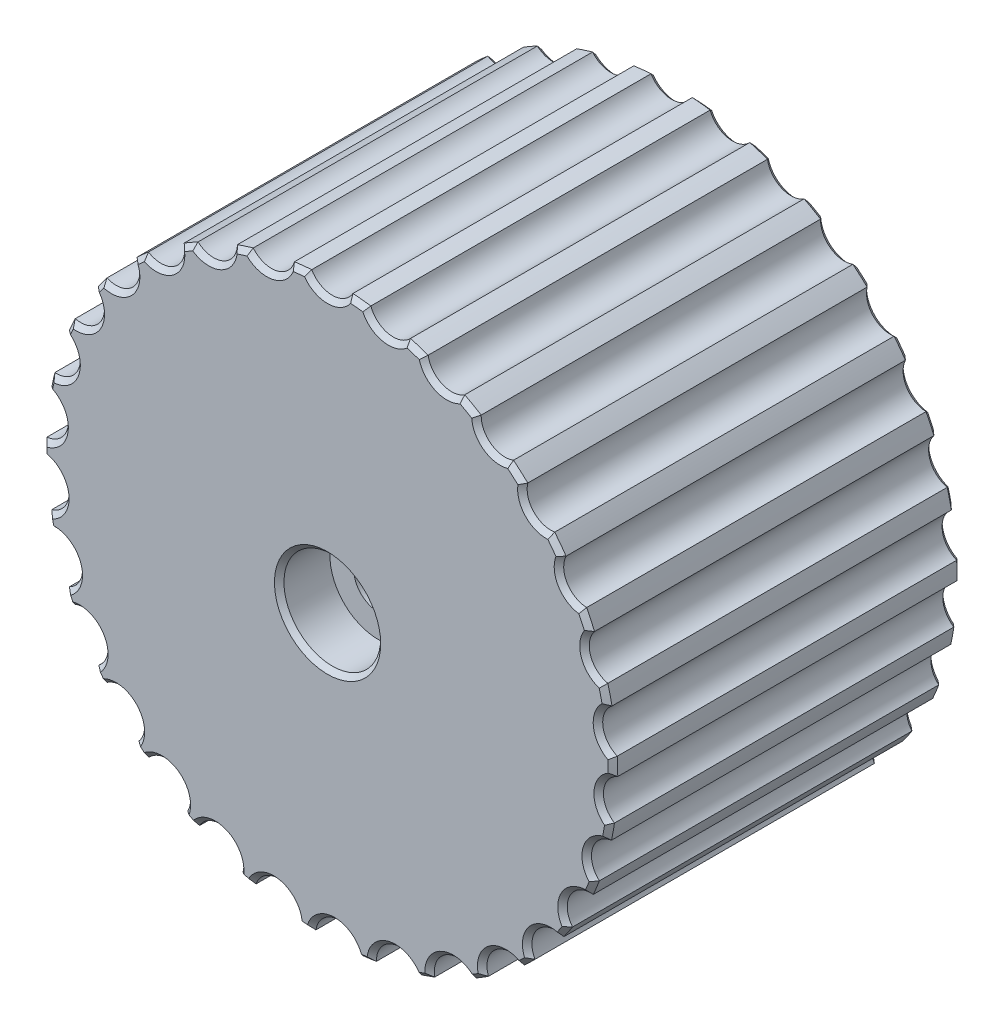
SolidWorks part; units mm, degrees
ref_plane "Ebene vorne" through (0, 0, 0) normal (0, 0, 1) x (1, 0, 0)
ref_plane "Ebene oben" through (0, 0, 0) normal (0, 1, 0) x (1, 0, 0)
ref_plane "Ebene rechts" through (0, 0, 0) normal (1, 0, 0) x (0, 0, -1)
sketch "Skizze1" plane through (0, 0, 0) normal (0, 0, 1) x (1, 0, 0)
  circle A0 centre (0, 0) radius 18
  dimension "D1" = 36
extrude "Grundkörper" add sketch "Skizze1" along normal blind 14
sketch "Skizze3" plane through (0, 0, 0) normal (0, 0, -1) x (-1, 0, 0)
  circle A0 centre (0, 0) radius 11.05
  dimension "D1" = 22.1
extrude "Sitz_Kugellager" cut sketch "Skizze3" against normal blind 7.5
sketch "Skizze4" plane through (0, 0, 0) normal (0, 0, -1) x (-1, 0, 0)
  circle A0 centre (0, 0) radius 15.6
  circle A1 centre (0, 0) radius 18
  circle A2 centre (0, 0) radius 18 construction
  dimension "D1" = 31.2
extrude "Sitz_SchneckenGehäuse" add sketch "Skizze4" along normal blind 8
sketch "Skizze5" plane through (0, 0, 14) normal (0, 0, 1) x (1, 0, 0)
  circle A0 centre (0, 0) radius 1.55
  dimension "D1" = 3.1
extrude "Bohrung M3 Zapfen" cut sketch "Skizze5" against normal through all
sketch "Skizze6" plane through (0, 0, 14) normal (0, 0, 1) x (1, 0, 0)
  circle A0 centre (0, 0) radius 3.05
  dimension "D1" = 6.1
extrude "Senkung M3" cut sketch "Skizze6" against normal blind 3.2
sketch "Skizze7" plane through (0, 0, 14) normal (0, 0, 1) x (1, 0, 0)
  line L0 (0, 18.7) -> (0, 0) construction
  circle A0 centre (0, 18.7) radius 1.5
  circle A2 centre (3.8409, 18.3436) radius 1.5
  circle A3 centre (7.5238, 17.1965) radius 1.5
  circle A4 centre (10.8876, 15.3087) radius 1.5
  circle A5 centre (13.7855, 12.7627) radius 1.5
  circle A6 centre (16.0907, 9.6699) radius 1.5
  circle A7 centre (17.7025, 6.1654) radius 1.5
  circle A8 centre (18.5505, 2.4024) radius 1.5
  circle A9 centre (18.5976, -1.4547) radius 1.5
  circle A10 centre (17.8417, -5.2373) radius 1.5
  circle A11 centre (16.3158, -8.7801) radius 1.5
  circle A12 centre (14.0867, -11.9282) radius 1.5
  circle A13 centre (11.2518, -14.5441) radius 1.5
  circle A14 centre (7.935, -16.5134) radius 1.5
  circle A15 centre (4.2813, -17.75) radius 1.5
  circle A16 centre (0.4502, -18.2) radius 1.5
  circle A17 centre (-3.3907, -17.8436) radius 1.5
  circle A18 centre (-7.0736, -16.6965) radius 1.5
  circle A19 centre (-10.4374, -14.8087) radius 1.5
  circle A20 centre (-13.3353, -12.2627) radius 1.5
  circle A21 centre (-15.6405, -9.1699) radius 1.5
  circle A22 centre (-17.2523, -5.6654) radius 1.5
  circle A23 centre (-18.1003, -1.9024) radius 1.5
  circle A24 centre (-18.1474, 1.9547) radius 1.5
  circle A25 centre (-17.3915, 5.7373) radius 1.5
  circle A26 centre (-15.8656, 9.2801) radius 1.5
  circle A27 centre (-13.6365, 12.4282) radius 1.5
  circle A28 centre (-10.8016, 15.0441) radius 1.5
  circle A29 centre (-7.4848, 17.0134) radius 1.5
  circle A30 centre (-3.8311, 18.25) radius 1.5
  circle A31 centre (0, 0) radius 18 construction
  point P2 (0, 18.7386)
  point P51 (0.2251, 0.25)
  dimension "D1" = 3
  dimension "D3" = 18.7
  dimension "D2" = 30
extrude "Schnitt-Linear austragen3" cut sketch "Skizze7" against normal through all
chamfer "Fase1" distance 0.3 angle 45 122 edges at (3.05, 0, 14) (-1.4624, -17.9405, 14) (-3.1107, -16.37, 14) (-5.2185, -17.2269, 14) (-6.4884, -15.3153, 14) (-8.7445, -15.7332, 14) (-9.5733, -13.5826, 14) (-11.8772, -13.5253, 14) (-12.2312, -11.2474, 14) (-14.4715, -10.704, 14) (-14.3465, -8.4113, 14) (-16.4085, -7.4001, 14) (-15.8272, -5.1975, 14) (-17.6015, -3.7667, 14) (-16.6085, -1.7456, 14) (-18, 0.0282, 14) (-16.656, 1.794, 14) (-17.5918, 3.8115, 14) (-15.967, 5.2674, 14) (-16.4027, 7.413, 14) (-14.5708, 8.5227, 14) (-14.4935, 10.6742, 14) (-12.5279, 11.4178, 14) (-11.9564, 13.4552, 14) (-9.9268, 13.8256, 14) (-8.9092, 15.6405, 14) (-6.8808, 15.6404, 14) (-5.4889, 17.1427, 14) (-3.5229, 16.782, 14) (-1.8452, 17.9052, 14) (0, 17.2, 14) (1.8661, 17.903, 14) (3.5335, 16.8755, 14) (5.4894, 17.1425, 14) (6.9225, 15.8222, 14) (8.8747, 15.6601, 14) (10.0183, 14.0863, 14) (11.8834, 13.5198, 14) (12.6848, 11.7437, 14) (14.3919, 10.8107, 14) (14.805, 8.8973, 14) (16.2963, 7.6441, 14) (16.286, 5.6721, 14) (17.5152, 4.1493, 14) (17.0629, 2.2098, 14) (17.9939, 0.4702, 14) (17.1021, -1.3377, 14) (17.706, -3.2399, 14) (16.4024, -4.8148, 14) (16.6565, -6.8235, 14) (14.9949, -8.0692, 14) (14.8823, -10.1251, 14) (12.942, -10.9589, 14) (12.4522, -12.9978, 14) (10.334, -13.3576, 14) (9.4655, -15.3103, 14) (7.2854, -15.1613, 14) (6.0488, -16.9532, 14) (3.9295, -16.2918, 14) (2.3512, -17.8458, 14) (0.4131, -16.7005, 14) (-15.6, 0, -8) (2.3512, -17.8458, -8) (3.9295, -16.2918, -8) (6.0488, -16.9532, -8) (7.2854, -15.1613, -8) (9.4655, -15.3103, -8) (10.334, -13.3576, -8) (12.4522, -12.9978, -8) (12.942, -10.9589, -8) (14.8823, -10.1251, -8) (14.9949, -8.0692, -8) (16.6565, -6.8235, -8) (16.4024, -4.8148, -8) (17.706, -3.2399, -8) (17.1021, -1.3377, -8) (17.9939, 0.4702, -8) (17.0629, 2.2098, -8) (17.5152, 4.1493, -8) (16.286, 5.6721, -8) (16.2963, 7.6441, -8) (14.805, 8.8973, -8) (14.3919, 10.8107, -8) (12.6848, 11.7437, -8) (11.8834, 13.5198, -8) (10.0183, 14.0863, -8) (8.8747, 15.6601, -8) (6.9225, 15.8222, -8) (5.4894, 17.1425, -8) (3.5335, 16.8755, -8) (1.8661, 17.903, -8) (0, 17.2, -8) (-1.8452, 17.9052, -8) (-3.5229, 16.782, -8) (-5.4889, 17.1427, -8) (-6.8808, 15.6404, -8) (-8.9092, 15.6405, -8) (-9.9268, 13.8256, -8) (-11.9564, 13.4552, -8) (-12.5279, 11.4178, -8) (-14.4935, 10.6742, -8) (-14.5708, 8.5227, -8) (-16.4027, 7.413, -8) (-15.967, 5.2674, -8) (-17.5918, 3.8115, -8) (-16.656, 1.794, -8) (-18, 0.0282, -8) (-16.6085, -1.7456, -8) (-17.6015, -3.7667, -8) (-15.8272, -5.1975, -8) (-16.4085, -7.4001, -8) (-14.3465, -8.4113, -8) (-14.4715, -10.704, -8) (-12.2312, -11.2474, -8) (-11.8772, -13.5253, -8) (-9.5733, -13.5826, -8) (-8.7445, -15.7332, -8) (-6.4884, -15.3153, -8) (-5.2185, -17.2269, -8) (-3.1107, -16.37, -8) (-1.4624, -17.9405, -8) (0.4131, -16.7005, -8)
sketch "Skizze8" plane through (0, 0, 0) normal (0, 0, -1) x (-1, 0, 0)
  line L0 (0, 0) -> (0, 11.05) construction
  line L1 (4.2287, 10.2089) -> (4.42, 10.6708)
  line L2 (-4.2287, 10.2089) -> (-4.42, 10.6708)
  line L3 (6.7268, 8.7666) -> (7.0312, 9.1632)
  line L4 (10.9555, 1.4423) -> (11.4512, 1.5076)
  line L5 (10.9555, -1.4423) -> (11.4512, -1.5076)
  line L6 (6.7268, -8.7666) -> (7.0312, -9.1632)
  line L7 (4.2287, -10.2089) -> (4.42, -10.6708)
  line L8 (-4.2287, -10.2089) -> (-4.42, -10.6708)
  line L9 (-6.7268, -8.7666) -> (-7.0312, -9.1632)
  line L10 (-10.9555, -1.4423) -> (-11.4512, -1.5076)
  line L11 (-10.9555, 1.4423) -> (-11.4512, 1.5076)
  line L12 (-6.7268, 8.7666) -> (-7.0312, 9.1632)
  circle A0 centre (0, 0) radius 11.05 construction
  arc A1 (-4.42, -10.6708) -> (4.42, -10.6708) centre (0, 0) ccw
  arc A3 (-4.2287, 10.2089) -> (-6.7268, 8.7666) centre (0, 0) ccw
  arc A4 (-10.9555, 1.4423) -> (-10.9555, -1.4423) centre (0, 0) ccw
  arc A5 (-6.7268, -8.7666) -> (-4.2287, -10.2089) centre (0, 0) ccw
  arc A6 (4.2287, -10.2089) -> (6.7268, -8.7666) centre (0, 0) ccw
  arc A7 (-11.4512, -1.5076) -> (-7.0312, -9.1632) centre (0, 0) ccw
  arc A8 (7.0312, -9.1632) -> (11.4512, -1.5076) centre (0, 0) ccw
  arc A9 (10.9555, -1.4423) -> (10.9555, 1.4423) centre (0, 0) ccw
  arc A10 (11.4512, 1.5076) -> (7.0312, 9.1632) centre (0, 0) ccw
  arc A11 (6.7268, 8.7666) -> (4.2287, 10.2089) centre (0, 0) ccw
  arc A12 (4.42, 10.6708) -> (-4.42, 10.6708) centre (0, 0) ccw
  arc A13 (-7.0312, 9.1632) -> (-11.4512, 1.5076) centre (0, 0) ccw
  point P23 (0, 0)
  dimension "D1" = 0.5
  dimension "D2" = 45
  dimension "D3" = 6
extrude "FreischnittKugellager" cut sketch "Skizze8" against normal up to surface (7.5 mm away) up to face at (-1.55, 0, 7.5)
chamfer "Fase2" distance 0.4 angle 45 6 edges at (11.05, 0, 0) (5.525, -9.5696, 0) (-5.525, -9.5696, 0) (-11.05, 0, 0) (-5.525, 9.5696, 0) (5.525, 9.5696, 0)
